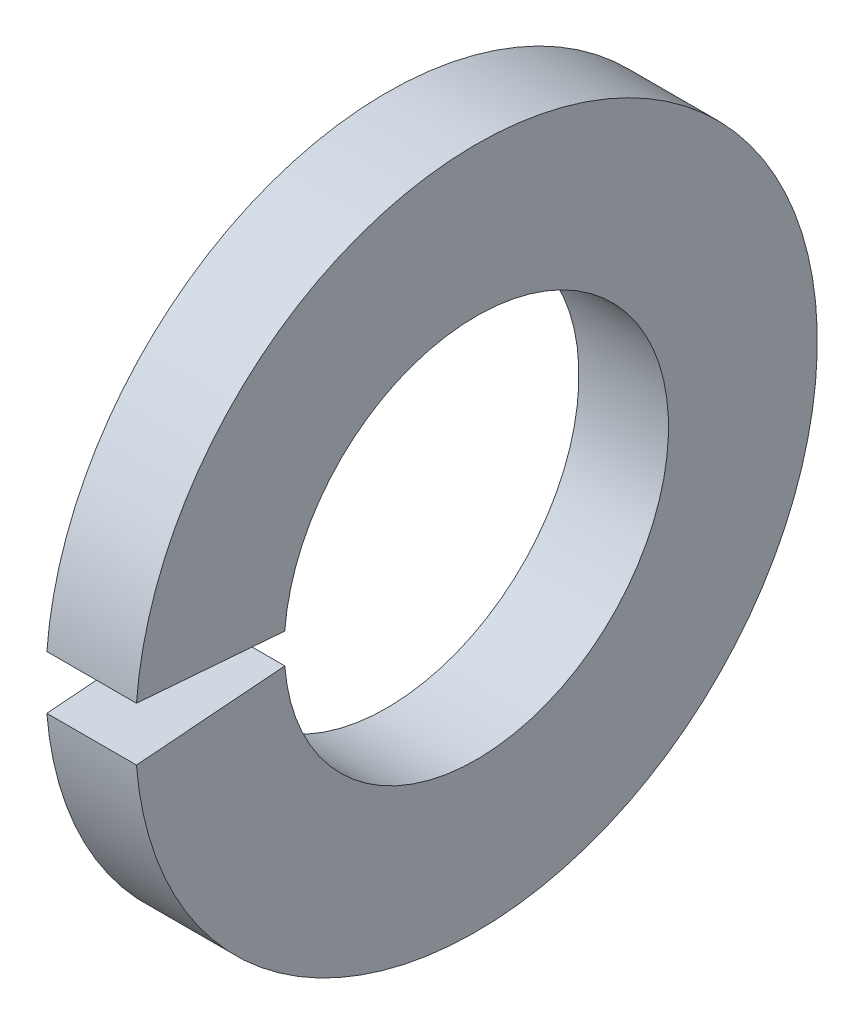
SolidWorks part; units mm, degrees
material "Alloy Steel"
ref_plane "Plane1" through (0, 0, 0) normal (0, 0, 1) x (1, 0, 0)
ref_plane "Plane2" through (0, 0, 0) normal (0, 1, 0) x (1, 0, 0)
ref_plane "Plane3" through (0, 0, 0) normal (1, 0, 0) x (0, 0, -1)
revolve "Base-Revolve" add sketch "Sketch1" angle 360 about L0
sketch "Sketch1" plane through (0, 0, 0) normal (0, 0, 1) x (1, 0, 0)
  line L0 (-34.925, 0) -> (9.525, 0) construction
  line L1 (0, 1.6891) -> (0, 2.9972)
  line L2 (0, 2.9972) -> (-0.7874, 2.9972)
  line L3 (-0.7874, 2.9972) -> (-0.7874, 1.6891)
  line L4 (-0.7874, 1.6891) -> (0, 1.6891)
  dimension "Thickness" = 0.7874
  dimension "Inside_dia" = 3.3782
  dimension "Outside_dia" = 5.9944
extrude "Gap" cut sketch "Sketch2" along normal through all
sketch "Sketch2" plane through (0, 0, 0) normal (-1, 0, 0) x (0, -1, 0)
  line L0 (0, 0) -> (0.2399, 3.0477)
  line L1 (0, -3.175) -> (0, 12.7) construction
  line L2 (0, 0) -> (-0.2399, 3.0477)
  arc A0 (0.2399, 3.0477) -> (-0.2399, 3.0477) centre (0, 0) ccw
  dimension "D1" = 3.0571
  dimension "Gap_ang" = 9
equation "\"D1@Sketch2\" = \"Outside_dia@Sketch1\" * 0.51"
